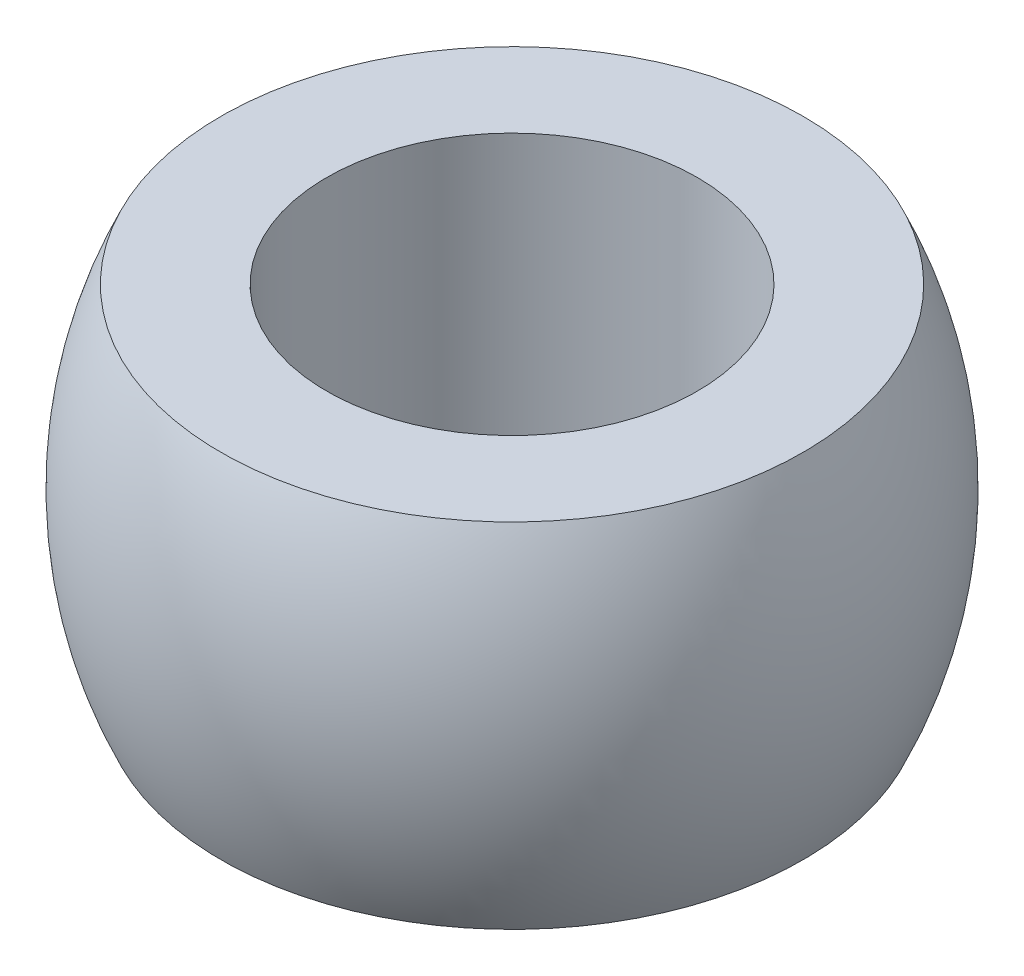
SolidWorks part; units mm, degrees
ref_plane "Płaszczyzna przednia" through (0, 0, 0) normal (0, 0, 1) x (1, 0, 0)
ref_plane "Płaszczyzna górna" through (0, 0, 0) normal (0, 1, 0) x (1, 0, 0)
ref_plane "Płaszczyzna prawa" through (0, 0, 0) normal (1, 0, 0) x (0, 0, -1)
sketch "Sketch1" plane through (0, 0, 0) normal (0, 0, 1) x (1, 0, 0)
  line L0 (0, 0) -> (0, 11.3433) construction
  line L1 (-5.25, 10) -> (-5.25, 0)
  line L2 (-5.25, 0) -> (-8.25, 0)
  line L3 (-5.25, 10) -> (-8.25, 10)
  line L4 (-10, 11.3433) -> (-10, 0) construction
  arc A0 (-8.25, 0) -> (-8.25, 10) centre (2.6587, 5) cw
  dimension "D2" = 10
  dimension "D5" = 12
  dimension "D1" = 5.25
  dimension "D3" = 3
  dimension "D4" = 3
  dimension "D6" = 10
revolve "Revolve1" add sketch "Sketch1" angle 360 about L0
